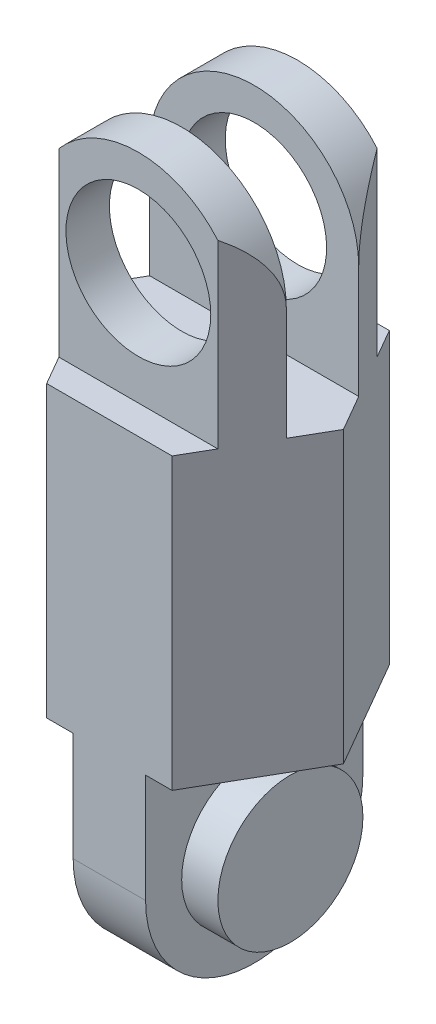
SolidWorks part; units mm, degrees
ref_plane "Alzado" through (0, 0, 0) normal (0, 0, 1) x (1, 0, 0)
ref_plane "Planta" through (0, 0, 0) normal (0, 1, 0) x (1, 0, 0)
ref_plane "Vista lateral" through (0, 0, 0) normal (1, 0, 0) x (0, 0, -1)
sketch "Croquis1" plane through (0, 0, 0) normal (0, 1, 0) x (1, 0, 0)
  line L1 (-17.3205, 0) -> (-8.6603, -15)
  line L2 (-8.6603, -15) -> (8.6603, -15)
  line L3 (8.6603, -15) -> (17.3205, 0)
  line L4 (17.3205, 0) -> (8.6603, 15)
  line L5 (8.6603, 15) -> (-8.6603, 15)
  line L6 (-8.6603, 15) -> (-17.3205, 0)
  circle A0 centre (0, 0) radius 15 construction
  dimension "D1" = 30
extrude "Saliente-Extruir1" add sketch "Croquis1" along normal mid plane 100
sketch "Croquis2" plane through (0, 0, 0) normal (0, 0, 1) x (1, 0, 0)
  line L1 (-17.3205, -50) -> (-5, -50)
  line L2 (-17.3205, -50) -> (-17.3205, -20)
  line L3 (-17.3205, -20) -> (-5, -20)
  line L4 (-5, -50) -> (-5, -20)
  line L5 (17.3205, -50) -> (5, -50)
  line L6 (17.3205, -50) -> (17.3205, -20)
  line L7 (17.3205, -20) -> (5, -20)
  line L8 (5, -50) -> (5, -20)
  dimension "D1" = 30
  dimension "D2" = 30
  dimension "D3" = 5
  dimension "D4" = 5
extrude "Cortar-Extruir1" cut sketch "Croquis2" against normal through all both and the other way through all
sketch "Croquis3" plane through (5, 0, 0) normal (1, 0, 0) x (0, 0, -1)
  line L0 (-15, -35) -> (-15, -53.0027)
  line L1 (-15, -20) -> (-15, -50) construction
  line L2 (-15, -53.0027) -> (15, -53.0027)
  line L3 (15, -53.0027) -> (15, -35)
  arc A0 (-15, -35) -> (15, -35) centre (0, -35) ccw
extrude "Cortar-Extruir2" cut sketch "Croquis3" against normal through all both and the other way through all
sketch "Croquis5" plane through (0, 0, 0) normal (1, 0, 0) x (0, 0, -1)
  circle A0 centre (0, -35) radius 10.0154
extrude "Saliente-Extruir2" add sketch "Croquis5" along normal mid plane 20
sketch "Croquis6" plane through (0, 0, 0) normal (1, 0, 0) x (0, 0, -1)
  line L0 (0, 50) -> (0, -20) construction
  line L1 (5, 20) -> (-5, 20)
  line L2 (5, 20) -> (5, 50)
  line L3 (5, 50) -> (-5, 50)
  line L4 (-5, 20) -> (-5, 50)
  line L5 (5, 20) -> (-5, 50) construction
  line L6 (5, 50) -> (-5, 20) construction
  line L7 (-15, 50) -> (0, 50) construction
  line L9 (-15, 50) -> (-11, 50)
  line L10 (-15, 50) -> (-15, 20)
  line L11 (-15, 20) -> (-11, 20)
  line L12 (-11, 50) -> (-11, 20)
  line L13 (15, 50) -> (11, 50)
  line L14 (15, 50) -> (15, 20)
  line L15 (15, 20) -> (11, 20)
  line L16 (11, 50) -> (11, 20)
  point P0 (0, 35)
  dimension "D1" = 10
  dimension "D2" = 30
  dimension "D3" = 4
  dimension "D4" = 4
extrude "Cortar-Extruir3" cut sketch "Croquis6" against normal through all both and the other way through all
sketch "Croquis7" plane through (0, 0, 0) normal (0, 0, 1) x (1, 0, 0)
  line L0 (-14.4338, 35.5662) -> (-14.4338, 54.062)
  line L1 (-14.4338, 54.062) -> (14.4338, 54.062)
  line L2 (14.4338, 54.062) -> (14.4338, 35.5662)
  arc A0 (14.4338, 35.5662) -> (-14.4338, 35.5662) centre (0, 35.5662) ccw
  circle A1 centre (0, 35.5662) radius 10
  dimension "D1" = 20
extrude "Cortar-Extruir4" cut sketch "Croquis7" against normal through all both and the other way through all
